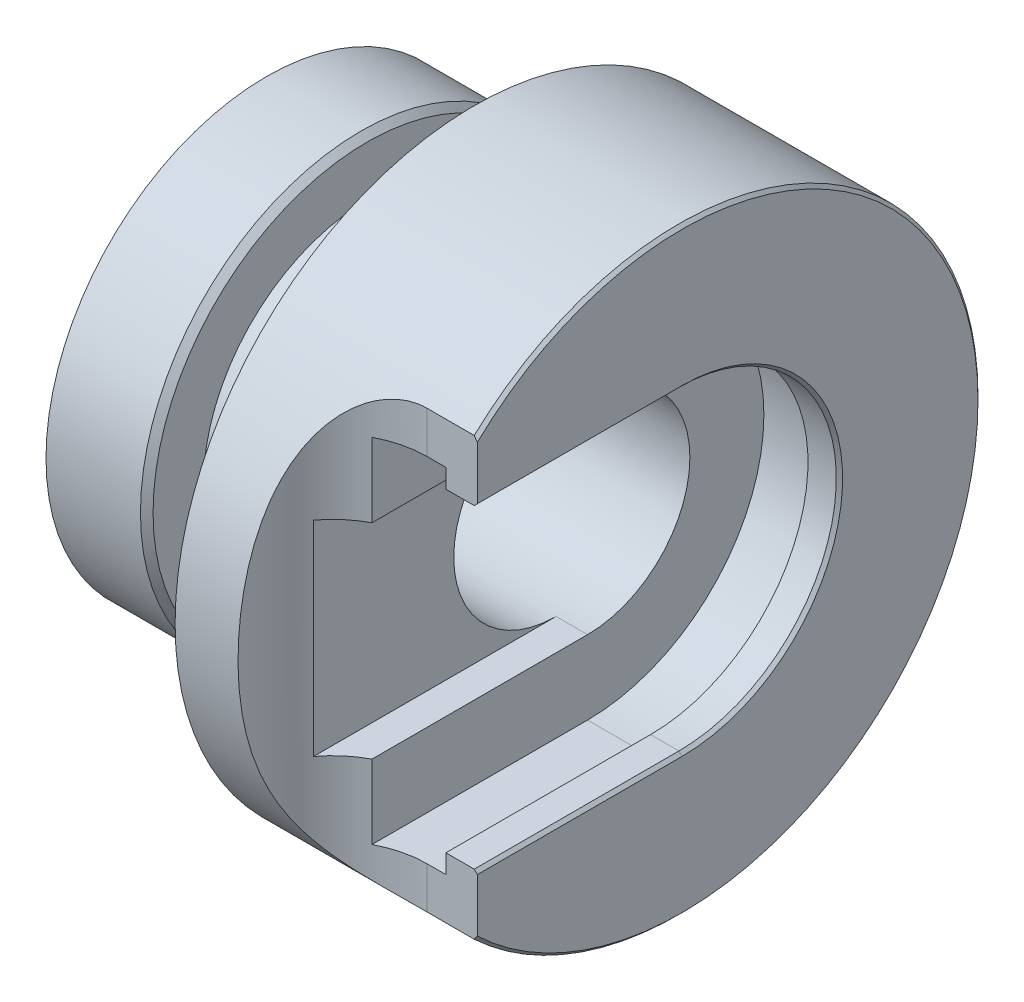
SolidWorks part; units mm, degrees
material "AISI 1020"
ref_plane "Plano superior" through (0, 0, 0) normal (0, 0, 1) x (1, 0, 0)
ref_plane "Plano frontal" through (0, 0, 0) normal (0, 1, 0) x (1, 0, 0)
ref_plane "Plano direito" through (0, 0, 0) normal (1, 0, 0) x (0, 0, -1)
sketch "Esboço1" plane through (0, 0, 0) normal (0, 0, 1) x (1, 0, 0)
  line L0 (0, 0) -> (23.3129, 0) construction
  line L1 (0, 0) -> (0, 6.5) construction
  line L2 (0, 3.25) -> (10.2, 3.25)
  line L3 (10.2, 3.25) -> (10.2, 5.6)
  line L4 (10.2, 5.6) -> (12.2, 5.6)
  line L5 (12.2, 5.6) -> (12.2, 5)
  line L6 (12.2, 5) -> (13.2, 5)
  line L7 (13.2, 5) -> (13.2, 9.5)
  line L8 (13.2, 9.5) -> (6.6, 9.5)
  line L9 (6.6, 9.5) -> (6.6, 5.2)
  line L10 (6.6, 5.2) -> (3.2, 5.2)
  line L11 (3.2, 5.2) -> (3.2, 7)
  line L12 (3.2, 7) -> (0, 7)
  line L13 (0, 7) -> (0, 3.25)
  dimension "D2" = 3.4
  dimension "D3" = 6.6
  dimension "D4" = 3.2
  dimension "D5" = 10.2
  dimension "D6" = 2
  dimension "D7" = 9.5
  dimension "D8" = 5.6
  dimension "D9" = 5
  dimension "D10" = 3.25
  dimension "D11" = 5.2
  dimension "D12" = 7
revolve "Revolução1" add sketch "Esboço1" angle 360 about L0
sketch "Esboço5" plane through (13.2, 0, 0) normal (1, 0, 0) x (0, 0, -1)
  line L0 (0, -5) -> (0, 5) construction
  line L2 (0, 5) -> (-9.5797, 5)
  line L3 (0, 5) -> (0, -5)
  line L4 (0, -5) -> (-9.5797, -5)
  line L5 (-9.5797, 5) -> (-9.5797, -5)
  circle A0 centre (0, 0) radius 5 construction
extrude "Corte-extrusão3" cut sketch "Esboço5" against normal blind 1.5
sketch "Esboço7" plane through (10.2, 0, 0) normal (1, 0, 0) x (0, 0, -1)
  line L0 (0, 0) -> (0, -5.6) construction
  line L1 (0, -5.6) -> (0, 5.6)
  line L3 (0, 5.6) -> (-9.6108, 5.6)
  line L4 (0, 5.6) -> (0, -5.6)
  line L5 (0, -5.6) -> (-9.6108, -5.6)
  line L6 (-9.6108, 5.6) -> (-9.6108, -5.6)
  circle A0 centre (0, 0) radius 5.6 construction
  point P7 (0, 0)
  circle M1 centre (0, 0) radius 5.6
extrude "Corte-extrusão4" cut sketch "Esboço7" along normal blind 2 contours L3 L6 L5 M1
sketch "Esboço8" plane through (10.2, 0, 0) normal (1, 0, 0) x (0, 0, -1)
  line L0 (0, -3.25) -> (0, 3.25) construction
  line L2 (0, 3.25) -> (-9.7043, 3.25)
  line L3 (0, 3.25) -> (0, -3.25)
  line L4 (0, -3.25) -> (-9.7043, -3.25)
  line L5 (-9.7043, 3.25) -> (-9.7043, -3.25)
  circle A0 centre (0, 0) radius 3.25 construction
extrude "Corte-extrusão5" cut sketch "Esboço8" against normal blind 1
chamfer "Chanfro2" distance 0.2 angle 45 1 edges at (3.2, 0, 7)
chamfer "Chanfro3" distance 0.1 angle 45 1 edges at (13.2, 0, -9.5)
chamfer "Chanfro4" distance 0.1 angle 45 3 edges at (13.2, 5, 3.9799) (13.2, -5, 3.9799) (13.2, 0, -5)
chamfer "Chanfro5" distance 1.5 angle 45 1 edges at (0, 0, 3.25)
sketch "Esboço9" plane through (0, 0, 0) normal (0, 1, 0) x (1, 0, 0)
  line L0 (11.6, -6.5) -> (13.2, -6.5)
  line L1 (11.6, -12.5) -> (13.2, -12.5)
  line L2 (13.2, -6.5) -> (13.2, -12.5)
  line L4 (6.6, 9.5) -> (6.6, -9.5) construction
  line L5 (6.6, -9.5) -> (9.2, -9.5) construction
  line L6 (6.6, -9.5) -> (9.2, -9.5) construction
  line L7 (13.2, -7.8962) -> (13.2, 9.4) construction
  arc A0 (11.6, -6.5) -> (11.6, -12.5) centre (11.6, -9.5) ccw
  dimension "D1" = 2
  dimension "D2" = 3
extrude "Corte-extrusão6" cut sketch "Esboço9" against normal through all both and the other way through all contours A0 L1 L2 L0
equation "\"1o\"=9.5"
